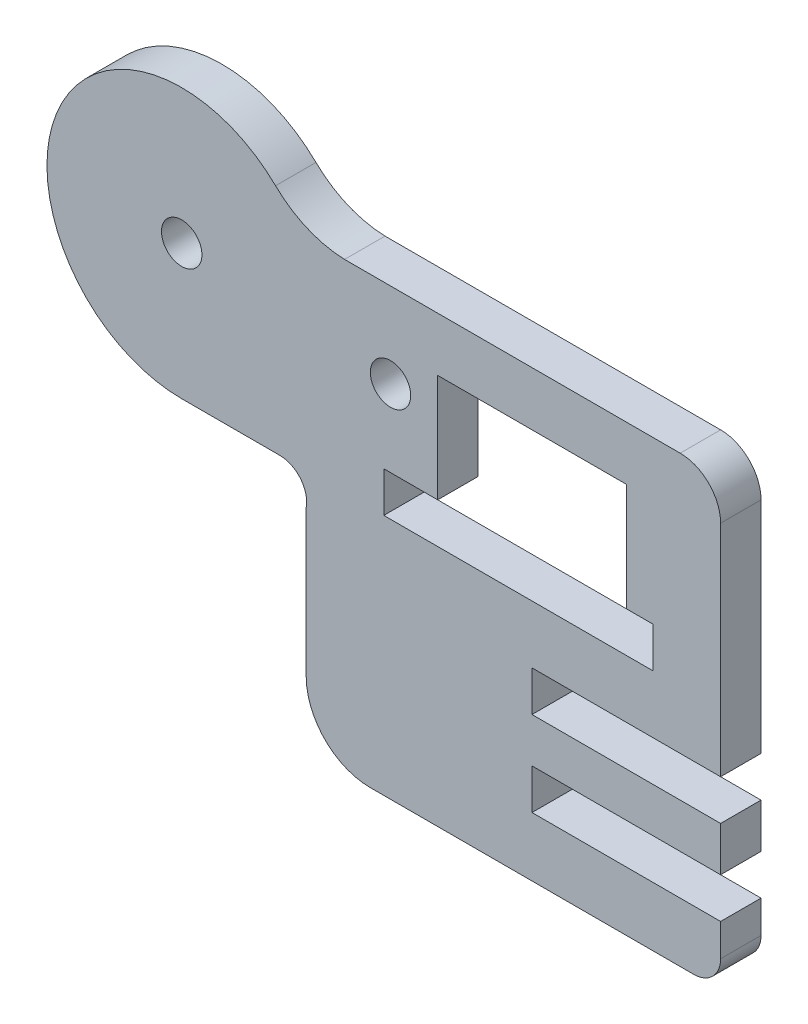
SolidWorks part; units mm, degrees
ref_plane "Front Plane" through (0, 0, 0) normal (0, 0, 1) x (1, 0, 0)
ref_plane "Top Plane" through (0, 0, 0) normal (0, 1, 0) x (1, 0, 0)
ref_plane "Right Plane" through (0, 0, 0) normal (1, 0, 0) x (0, 0, -1)
sketch "Sketch1" plane through (0, 0, 0) normal (0, 0, 1) x (1, 0, 0)
  line L1 (10.2706, 0.3316) -> (10.2706, -27.6684)
  line L2 (8.2706, -29.6684) -> (-15.7294, -29.6684)
  line L4 (-20.4875, -24.9103) -> (-20.4875, -14.0335)
  line L5 (-29.7294, -11.6684) -> (-22.4539, -11.6684)
  line L6 (-17.6384, 3.3316) -> (7.2706, 3.3316)
  arc A0 (-29.7294, 8.3316) -> (-39.7294, -1.6684) centre (-29.7294, -1.6684) ccw
  arc A1 (7.2706, 3.3316) -> (10.2706, 0.3316) centre (7.2706, 0.3316) cw
  arc A2 (10.2706, -27.6684) -> (8.2706, -29.6684) centre (8.2706, -27.6684) cw
  arc A6 (-20.4875, -24.9103) -> (-15.7294, -29.6684) centre (-15.7294, -24.9103) ccw
  arc A7 (-22.4539, -11.6684) -> (-20.4875, -14.0335) centre (-22.4539, -13.6684) cw
  arc A8 (-39.7294, -1.6684) -> (-29.7294, -11.6684) centre (-29.7294, -1.6684) ccw
  arc A9 (-29.7294, 8.3316) -> (-22.762, 5.5048) centre (-29.7294, -1.6684) cw
  arc A10 (-22.762, 5.5048) -> (-17.6384, 3.3316) centre (-17.3961, 11.0291) ccw
  dimension "D1" = 10
  dimension "D4" = 3
  dimension "D5" = 2
  dimension "D6" = 50
  dimension "D7" = 4.7581
  dimension "D9" = 2
  dimension "D3" = 10
  dimension "D8" = 10
  dimension "D11" = 7.7014
  dimension "D2" = 5
  dimension "D10" = 24
extrude "Boss-Extrude1" add sketch "Sketch1" along normal blind 3
sketch "Sketch2" plane through (0, 0, 3) normal (0, 0, 1) x (1, 0, 0)
  circle A0 centre (-29.7294, -1.6684) radius 1.5
  arc A1 (-22.762, 5.5048) -> (-29.7294, -11.6684) centre (-29.7294, -1.6684) ccw construction
  dimension "D1" = 3
extrude "Cut-Extrude1" cut sketch "Sketch2" against normal blind 3
sketch "Sketch3" plane through (0, 0, 3) normal (0, 0, 1) x (1, 0, 0)
  line L0 (7.2706, 3.3316) -> (-17.6384, 3.3316) construction
  line L1 (5.2706, -11.6684) -> (-14.7294, -11.6684)
  line L2 (5.2706, -11.6684) -> (5.2706, -8.6684)
  line L3 (5.2706, -8.6684) -> (-14.7294, -8.6684)
  line L4 (-14.7294, -11.6684) -> (-14.7294, -8.6684)
  line L6 (10.2706, -27.6684) -> (10.2706, 0.3316) construction
  line L7 (10.2706, -15.9684) -> (-3.7294, -15.9684)
  line L11 (10.2706, -18.9684) -> (10.2706, -15.9684)
  line L12 (-3.7294, -15.9684) -> (-3.7294, -18.9684)
  line L13 (-3.7294, -18.9684) -> (10.2706, -18.9684)
  line L16 (10.2706, -22.2684) -> (-3.7294, -22.2684)
  line L17 (10.2706, -22.2684) -> (10.2706, -25.2684)
  line L18 (10.2706, -25.2684) -> (-3.7294, -25.2684)
  line L19 (-3.7294, -22.2684) -> (-3.7294, -25.2684)
  dimension "D1" = 20
  dimension "D2" = 3
  dimension "D3" = 12
  dimension "D4" = 5
  dimension "D5" = 3
  dimension "D6" = 14
  dimension "D7" = 3
  dimension "D8" = 3.3
  dimension "D9" = 4.3
extrude "Cut-Extrude2" cut sketch "Sketch3" against normal blind 3
sketch "Sketch4" plane through (0, 0, 3) normal (0, 0, 1) x (1, 0, 0)
  line L0 (5.2706, -8.6684) -> (-14.7294, -8.6684) construction
  line L1 (3.2706, -8.6684) -> (-10.7294, -8.6684)
  line L2 (3.2706, -8.6684) -> (3.2706, -0.6684)
  line L3 (3.2706, -0.6684) -> (-10.7294, -0.6684)
  line L4 (-10.7294, -8.6684) -> (-10.7294, -0.6684)
  line L5 (10.2706, -15.9684) -> (10.2706, 0.3316) construction
  dimension "D1" = 8
  dimension "D2" = 7
  dimension "D3" = 14
extrude "Cut-Extrude3" cut sketch "Sketch4" against normal blind 3
sketch "Sketch5" plane through (0, 0, 3) normal (0, 0, 1) x (1, 0, 0)
  line L0 (-10.7294, -0.6684) -> (-10.7294, -8.6684) construction
  circle A0 centre (-14.2294, -2.9684) radius 1.5
  dimension "D1" = 3
  dimension "D2" = 5.7
  dimension "D3" = 3.5
extrude "Cut-Extrude4" cut sketch "Sketch5" against normal blind 3
